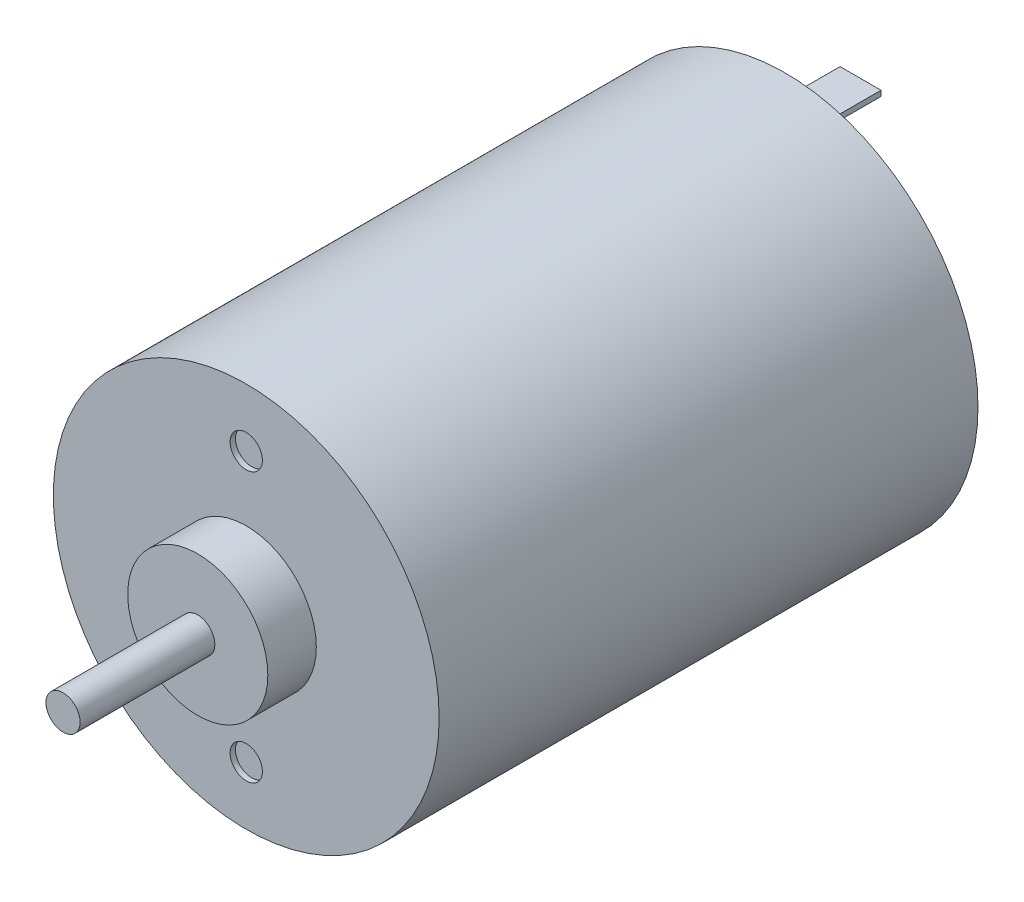
SolidWorks part; units mm, degrees
ref_plane "正面" through (0, 0, 0) normal (0, 0, 1) x (1, 0, 0)
ref_plane "平面" through (0, 0, 0) normal (0, 1, 0) x (1, 0, 0)
ref_plane "右側面" through (0, 0, 0) normal (1, 0, 0) x (0, 0, -1)
sketch "ｽｹｯﾁ2" plane through (0, 0, 0) normal (0, 0, 1) x (1, 0, 0)
  circle A0 centre (0, 0) radius 17.9
  dimension "D1" = 35.8
extrude "ﾎﾞｽ - 押し出し1" add sketch "ｽｹｯﾁ2" along normal blind 50
sketch "ｽｹｯﾁ3" plane through (0, 0, 50) normal (0, 0, 1) x (1, 0, 0)
  circle A0 centre (0, 0) radius 6.5
  dimension "D1" = 13
extrude "ﾎﾞｽ - 押し出し2" add sketch "ｽｹｯﾁ3" along normal blind 4.5
sketch "ｽｹｯﾁ4" plane through (0, 0, 54.5) normal (0, 0, 1) x (1, 0, 0)
  circle A0 centre (0, 0) radius 1.585
  dimension "D1" = 3.17
extrude "ﾎﾞｽ - 押し出し5" add sketch "ｽｹｯﾁ4" along normal blind 12.5
sketch "ｽｹｯﾁ5" plane through (0, 0, 50) normal (0, 0, 1) x (1, 0, 0)
  circle A0 centre (0, 12.5) radius 1.5
  circle A1 centre (0, -12.5) radius 1.5
  dimension "D1" = 3
  dimension "D2" = 25
  dimension "D3" = 12.5
extrude "ｶｯﾄ - 押し出し1" cut sketch "ｽｹｯﾁ5" against normal blind 0.5
sketch "ｽｹｯﾁ6" plane through (0, 0, 0) normal (0, 0, -1) x (-1, 0, 0)
  line L0 (19.69, 0) -> (-19.69, 0) construction
  line L1 (-1.9, 13.95) -> (1.9, 13.95)
  line L2 (-1.9, 13.95) -> (-1.9, 13.45)
  line L3 (-1.9, 13.45) -> (1.9, 13.45)
  line L4 (1.9, 13.95) -> (1.9, 13.45)
  line L5 (-1.9, 13.95) -> (1.9, 13.45) construction
  line L6 (-1.9, 13.45) -> (1.9, 13.95) construction
  line L11 (-1.9, -13.45) -> (1.9, -13.45)
  line L12 (1.9, -13.95) -> (1.9, -13.45)
  line L13 (-1.9, -13.95) -> (1.9, -13.95)
  line L14 (-1.9, -13.95) -> (-1.9, -13.45)
  point P4 (0, 13.7)
  point P5 (0, 0)
  dimension "D1" = 0.5
  dimension "D2" = 3.8
  dimension "D3" = 13.7
extrude "ﾎﾞｽ - 押し出し6" add sketch "ｽｹｯﾁ6" along normal blind 7
